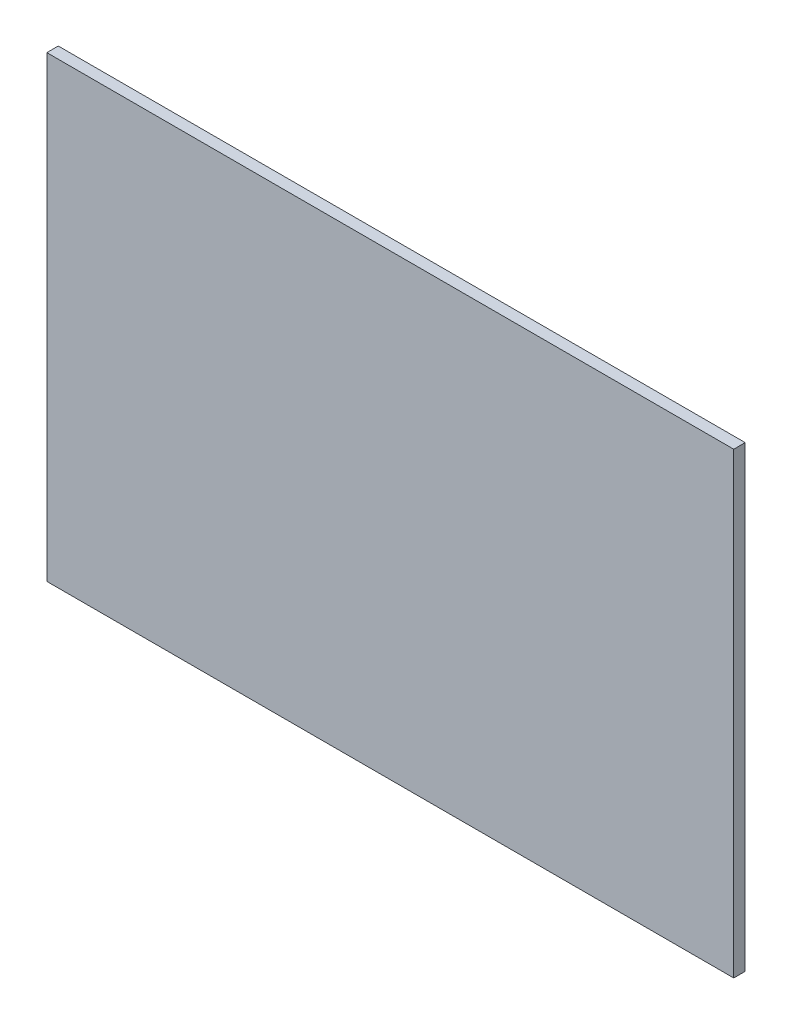
SolidWorks part; units mm, degrees
ref_plane "Ön Düzlem" through (0, 0, 0) normal (0, 0, 1) x (1, 0, 0)
ref_plane "Üst Düzlem" through (0, 0, 0) normal (0, 1, 0) x (1, 0, 0)
ref_plane "Sağ Düzlem" through (0, 0, 0) normal (1, 0, 0) x (0, 0, -1)
sketch "Sketch1" plane through (0, 0, 0) normal (0, 0, 1) x (1, 0, 0)
  line L1 (-240, 160) -> (240, 160)
  line L2 (-240, 160) -> (-240, -160)
  line L3 (-240, -160) -> (240, -160)
  line L4 (240, 160) -> (240, -160)
  line L5 (-240, 160) -> (240, -160) construction
  line L6 (-240, -160) -> (240, 160) construction
  point P0 (0, 0)
  dimension "D1" = 480
  dimension "D2" = 320
extrude "Boss-Extrude1" add sketch "Sketch1" along normal blind 8
